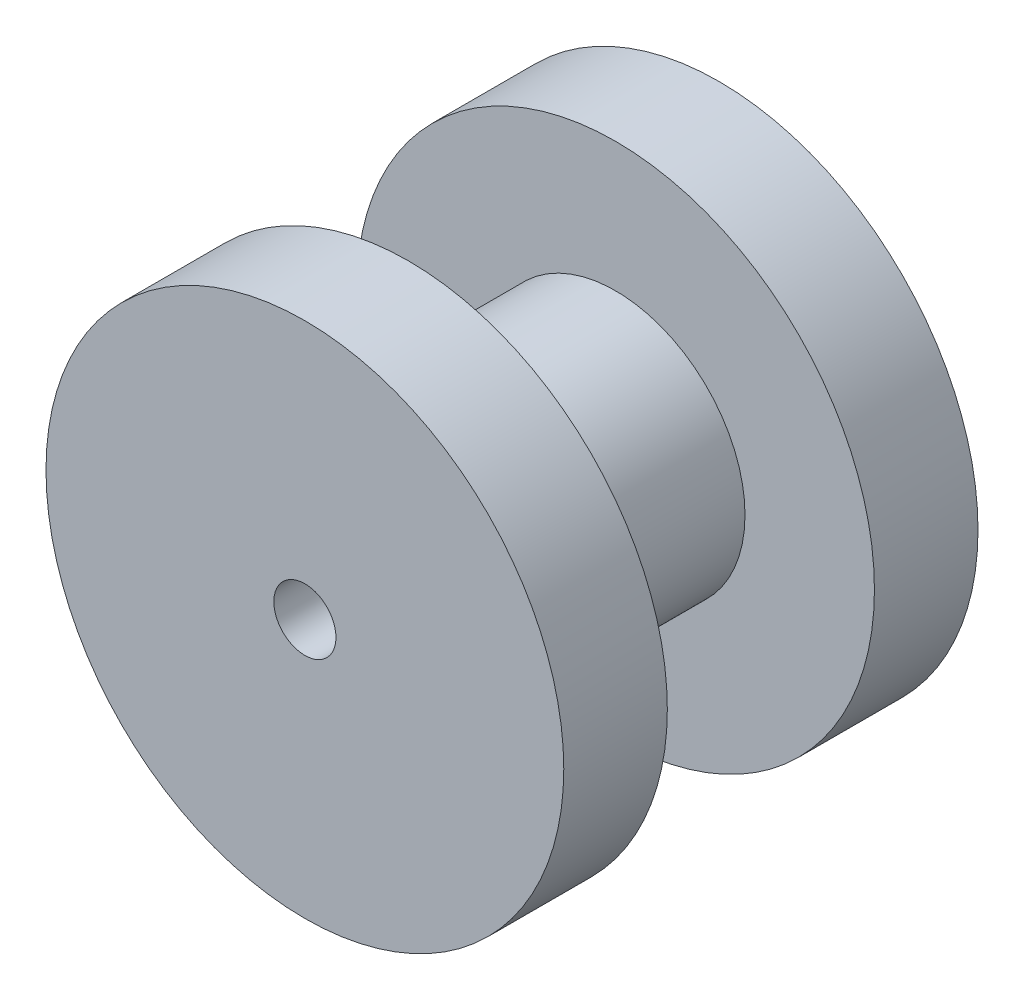
SolidWorks part; units mm, degrees
ref_plane "Front Plane" through (0, 0, 0) normal (0, 0, 1) x (1, 0, 0)
ref_plane "Top Plane" through (0, 0, 0) normal (0, 1, 0) x (1, 0, 0)
ref_plane "Right Plane" through (0, 0, 0) normal (1, 0, 0) x (0, 0, -1)
sketch "Sketch1" plane through (0, 0, 0) normal (0, 0, 1) x (1, 0, 0)
  circle A0 centre (0, 0) radius 50
  dimension "D1" = 100
extrude "Boss-Extrude1" add sketch "Sketch1" along normal blind 20
sketch "Sketch2" plane through (0, 0, 0) normal (0, 0, -1) x (-1, 0, 0)
  circle A0 centre (0, 0) radius 25
  dimension "D1" = 50
extrude "Boss-Extrude2" add sketch "Sketch2" along normal blind 40
sketch "Sketch3" plane through (0, 0, -40) normal (0, 0, -1) x (-1, 0, 0)
  circle A0 centre (0, 0) radius 50
  dimension "D1" = 100
extrude "Boss-Extrude3" add sketch "Sketch3" along normal blind 20
sketch "Sketch4" plane through (0, 0, 20) normal (0, 0, 1) x (1, 0, 0)
  circle A0 centre (0, 0) radius 6
  dimension "D1" = 12
extrude "Cut-Extrude1" cut sketch "Sketch4" against normal through all
ref_plane "Plane1" through (0, 0, -20) normal (0, 0, 1) x (1, 0, 0)
sketch "Sketch5" plane through (0, 0, -20) normal (0, 0, 1) x (1, 0, 0)
  point P0 (0, 0)
